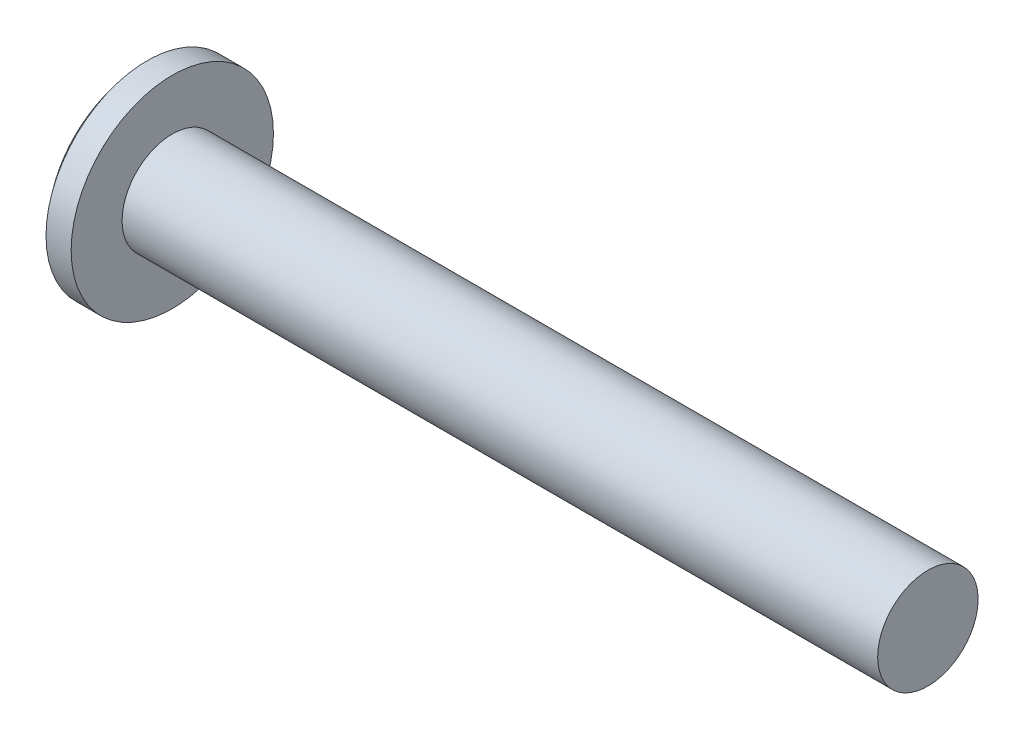
SolidWorks part; units mm, degrees
ref_plane "Plane1" through (0, 0, 0) normal (0, 0, 1) x (1, 0, 0)
ref_plane "Plane2" through (0, 0, 0) normal (0, 1, 0) x (1, 0, 0)
ref_plane "Plane3" through (0, 0, 0) normal (1, 0, 0) x (0, 0, -1)
other "Configuration Table"
sketch "BodySke" plane through (0, 0, 0) normal (0, 0, 1) x (1, 0, 0)
  line L0 (3.4036, 2.7432) -> (3.4036, 5.525)
  line L1 (44.6786, 0) -> (0, 0)
  line L2 (-25.4, 0) -> (127, 0) construction
  line L3 (2.0298, -5.525) -> (3.4036, -5.525) construction
  line L4 (3.4036, 2.7432) -> (44.6786, 2.7432)
  line L5 (44.6786, 2.7432) -> (44.6786, 0)
  line L6 (2.0298, 5.525) -> (3.4036, 5.525)
  line L7 (3.4036, -2.7432) -> (44.6786, -2.7432) construction
  line L8 (4.4628, 4.3307) -> (4.4628, -5.1943) construction
  line L9 (3.4036, 6.35) -> (3.4036, -3.175) construction
  arc A0 (2.0298, 5.525) -> (0, 0) centre (8.5344, 0) ccw
  dimension "Head_rad" = 8.5344
  dimension "Diameter" = 5.4864
  dimension "Length" = 41.275
  dimension "Head_ht" = 3.4036
  dimension "Head_dia" = 11.05
  dimension "Advance" = 1.0592
  dimension "Thread_nom" = 41.275
revolve "Base-Revolve" add sketch "BodySke" angle 360 about L2
cosmetic thread "ThreadCosmetic" [suppressed] parameters "Thread_length"=40.2158, "Thread_minor"=4.2266
sketch "Sketch2" plane through (0, 0, 0) normal (1, 0, 0) x (0, 0, -1)
  line L0 (5.525, -0.8509) -> (-5.525, -0.8509)
  line L1 (5.525, -0.8509) -> (5.525, 0.8509)
  line L2 (-5.525, 0.8509) -> (5.525, 0.8509)
  line L3 (-5.525, 0.8509) -> (-5.525, -0.8509)
  dimension "D1" = 11.05
  dimension "Slot_width" = 1.7018
  dimension "D2" = 5.525
  dimension "D3" = 0.8509
extrude "Slot" [suppressed] cut sketch "Sketch2" along normal blind 1.9558
sketch "Sketch3" plane through (0, 0, 0) normal (1, 0, 0) x (0, 0, -1)
  line L0 (0.6477, -3.6322) -> (-0.6477, -3.6322)
  line L1 (0.6477, -3.6322) -> (0.6477, 3.6322)
  line L2 (-0.6477, 3.6322) -> (0.6477, 3.6322)
  line L3 (-0.6477, 3.6322) -> (-0.6477, -3.6322)
  dimension "Cross_width" = 1.2954
  dimension "Cross_dia" = 7.2644
  dimension "D1" = 0.6477
  dimension "D2" = 3.6322
ref_plane "Plane4" through (4.2418, 0, 0) normal (1, 0, 0) x (0, 0, -1)
sketch "Sketch4" plane through (4.2418, 0, 0) normal (1, 0, 0) x (0, 0, -1)
  line L0 (0.3238, -0.3238) -> (-0.3238, -0.3239)
  line L1 (0.3238, -0.3238) -> (0.3238, 0.3238)
  line L2 (-0.3238, 0.3238) -> (0.3238, 0.3238)
  line L3 (-0.3238, 0.3238) -> (-0.3238, -0.3239)
  dimension "D1" = 0.6477
  dimension "D2" = 0.3238
  dimension "D3" = 0.6477
  dimension "D4" = 0.3238
loft "Cross" cut profiles "Sketch3", "Sketch4"
pattern_circular "CirPattern1" count 2 every 90 about axis through (0, 0, 0) along (1, 0, 0) of "Cross"
sketch "ThdSchSke" plane through (0, 0, 0) normal (0, 0, 1) x (1, 0, 0)
  line L0 (4.4628, -2.1133) -> (4.0217, -2.7432)
  line L1 (4.4628, -2.1133) -> (4.9039, -2.7432)
  line L2 (4.9039, -2.7432) -> (4.9039, -3.429)
  line L3 (-3.175, 0) -> (5.1513, 0) construction
  line L5 (4.9039, -3.429) -> (4.0217, -3.429)
  line L6 (4.0217, -3.429) -> (4.0217, -2.7432)
  dimension "Diameter" = 5.4864
  dimension "SideAngle" = 55
  dimension "VeeAngle" = 70
  dimension "Thread_minor" = 4.2266
  dimension "Overcut" = 6.858
  dimension "Start" = 4.4628
revolve "ThreadSchematic" [suppressed] cut sketch "ThdSchSke" angle 360 about L3
pattern_linear "ThdSchPat" [suppressed]
equation "\"D1@Sketch2\" = \"Head_dia@BodySke\""
equation "\"D2@Sketch2\" = \"D1@Sketch2\" / 2"
equation "\"D3@Sketch2\" = \"Slot_width@Sketch2\" / 2"
equation "\"D1@Sketch3\" = \"Cross_width@Sketch3\" / 2"
equation "\"D2@Sketch3\" = \"Cross_dia@Sketch3\" / 2"
equation "\"D1@Sketch4\" = \"Cross_width@Sketch3\" *.5"
equation "\"D2@Sketch4\" = \"D1@Sketch4\" / 2"
equation "\"D3@Sketch4\" = \"D1@Sketch4\""
equation "\"D4@Sketch4\" = \"D3@Sketch4\" / 2"
equation "\"Thread_length@ThreadCosmetic\" = ((sgn( (\"Length@BodySke\" - \"Advance@BodySke\" ) - \"Thread_nom@BodySke\" )-1)*( (\"Length@BodySke\" - \"Advance@BodySke\" ) - \"Thread_nom@BodySke\" ))/-2+ \"Thread_nom@BodySke\""
equation "\"Thread_minor@ThdSchSke\" = \"Thread_minor@ThreadCosmetic\""
equation "\"Diameter@ThdSchSke\" = \"Diameter@BodySke\""
equation "\"Overcut@ThdSchSke\" = \"Diameter@BodySke\" * 1.25"
equation "\"Start@ThdSchSke\" = \"Head_ht@BodySke\" + \"Length@BodySke\" - \"Thread_length@ThreadCosmetic\"  '---Non-countersunk---"
equation "\"Num_threads@ThdSchPat\" = int( \"Thread_length@ThreadCosmetic\" / \"Advance@BodySke\" + 0.999 )  + 1"
equation "\"Advance@ThdSchPat\" = \"Thread_length@ThreadCosmetic\" /  (\"Num_threads@ThdSchPat\" - 1) 'relax it"
